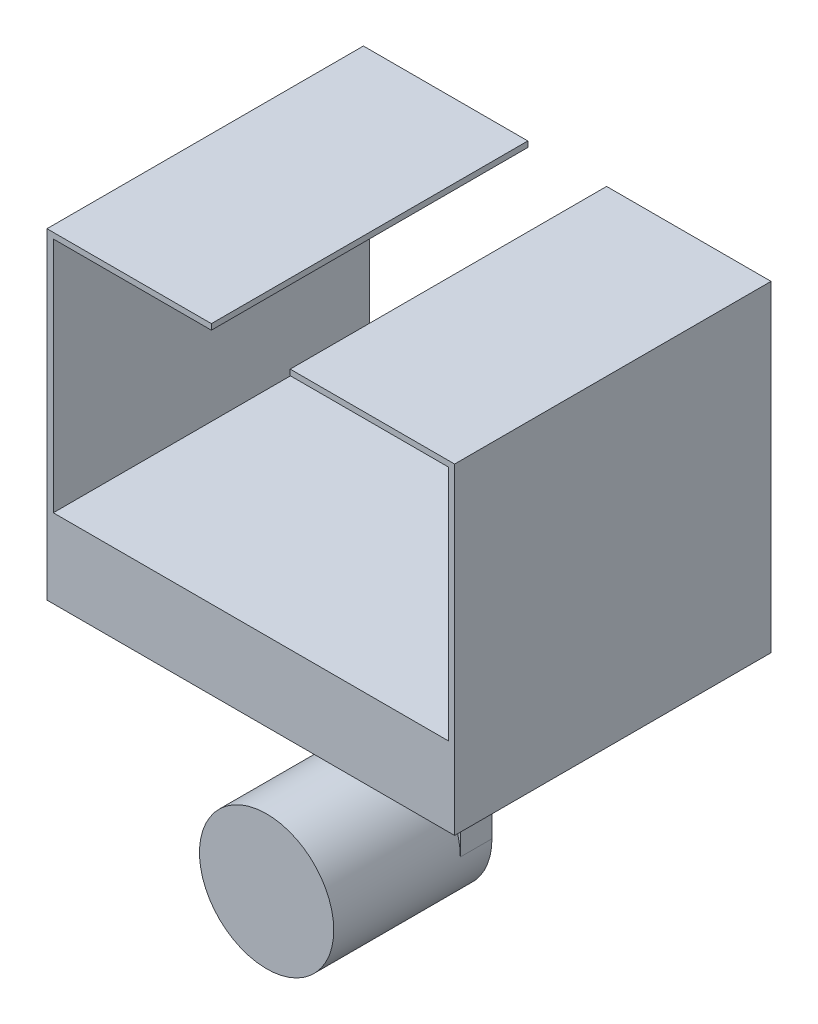
SolidWorks part; units mm, degrees
material "6061-T6 (SS)"
ref_plane "Front Plane" through (0, 0, 0) normal (0, 0, 1) x (1, 0, 0)
ref_plane "Top Plane" through (0, 0, 0) normal (0, 1, 0) x (1, 0, 0)
ref_plane "Right Plane" through (0, 0, 0) normal (1, 0, 0) x (0, 0, -1)
sketch "Sketch1" plane through (0, 0, 0) normal (0, 0, 1) x (1, 0, 0)
  circle A0 centre (0, 0) radius 10.7776
  dimension "D1" = 21.5551
extrude "Boss-Extrude1" add sketch "Sketch1" against normal blind 25.4
sketch "Sketch2" plane through (0, 0, -25.4) normal (0, 0, -1) x (-1, 0, 0)
  line L0 (-10.7776, 0) -> (10.7776, 0)
  line L1 (10.7776, 0) -> (10.7776, 25.4)
  line L2 (10.7776, 25.4) -> (-10.7776, 25.4)
  line L3 (-10.7776, 0) -> (-10.7776, 25.4)
  circle A0 centre (0, 0) radius 10.7776 construction
  dimension "D1" = 25.4
extrude "Boss-Extrude2" add sketch "Sketch2" against normal blind 5.08
sketch "Sketch6" plane through (0, 25.4, 0) normal (0, 1, 0) x (1, 0, 0)
  line L0 (-10.7776, 22.86) -> (10.7776, 22.86) construction
  line L1 (-10.7776, 20.32) -> (-10.7776, 25.4) construction
  line L2 (10.7776, 20.32) -> (10.7776, 25.4) construction
  line L3 (0, 22.86) -> (0, 25.4) construction
  line L6 (-10.7776, 25.4) -> (10.7776, 25.4) construction
  line L7 (-32.721, 48.26) -> (32.721, 48.26)
  line L8 (-32.721, 48.26) -> (-32.721, -2.54)
  line L9 (-32.721, -2.54) -> (32.721, -2.54)
  line L10 (32.721, 48.26) -> (32.721, -2.54)
  line L11 (0, 25.4) -> (0, 20.32) construction
  line L12 (-10.7776, 20.32) -> (10.7776, 20.32) construction
  dimension "D1" = 50.8
  dimension "D2" = 65.4419
extrude "Boss-Extrude3" add sketch "Sketch6" along normal blind 51.6394
sketch "Sketch7" plane through (0, 0, 2.54) normal (0, 0, 1) x (1, 0, 0)
  line L0 (-10.7776, 25.4) -> (10.7776, 25.4) construction
  line L1 (-31.7043, 38.0492) -> (31.7043, 38.0492)
  line L2 (-31.7043, 38.0492) -> (-31.7043, 76.1238)
  line L3 (-31.7043, 76.1238) -> (31.7043, 76.1238)
  line L4 (31.7043, 38.0492) -> (31.7043, 76.1238)
  line L5 (0, 77.0394) -> (0, 25.4) construction
  line L6 (-32.721, 77.0394) -> (32.721, 77.0394) construction
  line L7 (-32.721, 25.4) -> (32.721, 25.4) construction
  line L8 (-32.721, 51.2197) -> (32.721, 51.2197) construction
  line L9 (-32.721, 77.0394) -> (-32.721, 25.4) construction
  line L10 (32.721, 77.0394) -> (32.721, 25.4) construction
  dimension "D1" = 12.6492
  dimension "D2" = 63.4086
  dimension "D3" = 38.0746
extrude "Cut-Extrude1" cut sketch "Sketch7" against normal through all
sketch "Sketch8" plane through (0, 0, 2.54) normal (0, 0, 1) x (1, 0, 0)
  line L0 (31.7043, 76.1238) -> (-31.7043, 76.1238) construction
  line L1 (-6.3246, 76.1238) -> (6.3246, 76.1238)
  line L2 (-6.3246, 76.1238) -> (-6.3246, 77.0394)
  line L3 (-6.3246, 77.0394) -> (6.3246, 77.0394)
  line L4 (6.3246, 76.1238) -> (6.3246, 77.0394)
  line L5 (-32.721, 77.0394) -> (32.721, 77.0394) construction
  line L6 (0, 38.0492) -> (0, 76.1238) construction
  line L7 (-31.7043, 38.0492) -> (31.7043, 38.0492) construction
  dimension "D2" = 12.6492
extrude "Cut-Extrude2" cut sketch "Sketch8" against normal through all
equation "\"F\"= 600'applied force (lbf)"
equation "\"SF\"= 4'Safety Factor"
equation "\"Sy\"= 40000'Yield Strength (PSI)"
equation "\"La\"= 1in'Feature A length"
equation "\"Ma\"= \"F\" * \"La\"'lbf in"
equation "\"Za\"= \"SF\" * \"Ma\" / \"Sy\"'Section Modulus (in^3)"
equation "\"ra\"= ( 4 * \"Za\" / pi ) ^ ( 1 / 3 )'RADIUS A"
equation "\"D\"= \"ra\" * 2'DIAMETER A"
equation "\"P_B\"= \"F\" * 2' FEATURE B AXIAL LOAD LBF"
equation "\"ALLOWSTRESS\"= \"Sy\" / \"SF\"'ALLOWABLE NORMAL STRESS"
equation "\"A_B\"= \"P_B\" / \"ALLOWSTRESS\"'FEATURE B REQUIRED AREA IN^2"
equation "\"T_B\" = 0.2in'FEATURE B REQUIRED THICKNESS"
equation "\"L_B\"= 1in'LENGTH OF B"
equation "\"L_C\"= \"A_FIT\" + \"B_FIT\" * 2'FEATURE C SPAN"
equation "\"B_C\"= 2in'BRACKET DEPTH"
equation "\"M_C\"= \"P_B\" * \"L_C\" / 4'MAX BENDING MOMENT"
equation "\"Z_C\"= \"M_C\" / \"ALLOWSTRESS\"'REQUIRED SECTION MODULUS IN^3"
equation "\"H_C\"= sqr ( 6 * \"Z_C\" / \"B_C\" )'required c thickness"
equation "\"P_D\"= \"F\"'FEATURE D AXIAL LOAD LBF"
equation "\"A_D\"= \"P_D\" / \"ALLOWSTRESS\"'FEATURE D REQUIRED AREA "
equation "\"P_E\"= \"F\"'E AXIAL LOAD LBF"
equation "\"A_E\"= \"P_E\" / \"ALLOWSTRESS\"'FEATURE E REQUIRED AREA"
equation "\"A_FIT\"= 0.498IN'T BEAM INTERFACE DIM A"
equation "\"B_FIT\"= 0.9992in'T BEAM INTERFACE DIM B"
equation "\"C_FIT\"= 1.499in'T BEAM INTERFACE DIM C"
equation "\"T_D\"= \"A_D\" / \"C_FIT\"'FEATURE D REQUIRED THIVKNESS"
equation "\"T_E\"= \"A_E\" / \"B_FIT\"'FEATURE E REQUIRED THICKNESS"
equation "\"OVERALLWIDTH\"= \"L_C\" + \"T_D\" * 2'SLECTED OVERALL BRACKET WIDTH"
equation "\"OVERALLHEIGHT\"= \"H_C\" + \"T_E\" + \"C_FIT\""
equation "\"D1@Boss-Extrude2\"= \"T_B\""
equation "\"D1@Sketch1\"= \"D\""
equation "\"D1@Boss-Extrude1\"= \"La\""
equation "\"D1@Sketch2\"= \"L_B\""
equation "\"D1@Sketch6\"= \"B_C\""
equation "\"D2@Sketch6\"= \"OVERALLWIDTH\""
equation "\"D1@Boss-Extrude3\"= \"OVERALLHEIGHT\""
equation "\"D1@Sketch7\"= \"A_FIT\""
equation "\"D2@Sketch7\"= \"L_C\""
equation "\"D3@Sketch7\"= \"C_FIT\""
